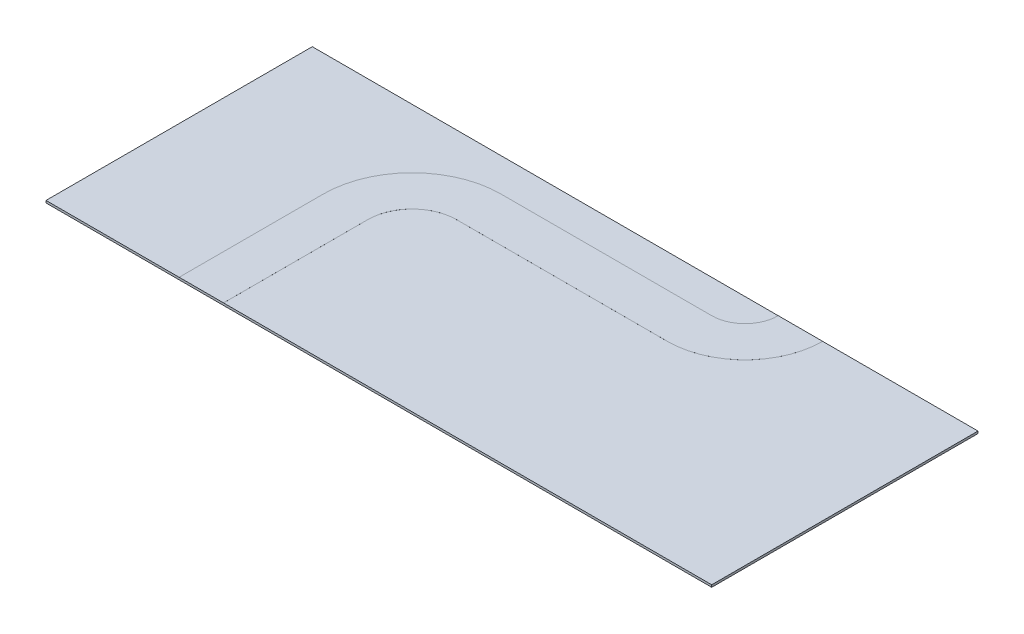
SolidWorks part; units mm, degrees
other "Kamera1"
ref_plane "Ebene vorne" through (0, 0, 0) normal (0, 0, 1) x (1, 0, 0)
ref_plane "Ebene oben" through (0, 0, 0) normal (0, 1, 0) x (1, 0, 0)
ref_plane "Ebene rechts" through (0, 0, 0) normal (1, 0, 0) x (0, 0, -1)
sketch "Skizze1" plane through (0, 0, 0) normal (0, 1, 0) x (1, 0, 0)
  line L1 (-1500, 600) -> (1500, 600)
  line L2 (-1500, 600) -> (-1500, -600)
  line L3 (-1500, -600) -> (1500, -600)
  line L4 (1500, 600) -> (1500, -600)
  line L5 (-1500, 600) -> (1500, -600) construction
  line L6 (-1500, -600) -> (1500, 600) construction
  point P0 (0, 0)
  dimension "D1" = 3000
  dimension "D2" = 1200
extrude "Boden" add sketch "Skizze1" along normal blind 10
sketch "Skizze2" plane through (0, 10, 0) normal (0, 1, 0) x (1, 0, 0)
  line L0 (-800, -600) -> (-800, 50) construction
  line L1 (-1500, -600) -> (1500, -600) construction
  line L2 (-500, 350) -> (450, 350) construction
  line L3 (1500, 600) -> (-1500, 600) construction
  line L6 (-700, -600) -> (-700, 50)
  line L7 (-500, 250) -> (450, 250)
  line L8 (-900, -600) -> (-900, 50)
  line L9 (-500, 450) -> (450, 450)
  line L10 (0, 0) -> (0, 756.6063) construction
  line L11 (800, 600) -> (600, 600)
  line L12 (-700, -600) -> (-900, -600)
  arc A0 (-800, 50) -> (-500, 350) centre (-500, 50) cw construction
  arc A1 (450, 350) -> (700, 600) centre (450, 600) ccw construction
  arc A2 (-700, 50) -> (-500, 250) centre (-500, 50) cw
  arc A3 (450, 250) -> (800, 600) centre (450, 600) ccw
  arc A4 (-900, 50) -> (-500, 450) centre (-500, 50) cw
  arc A5 (450, 450) -> (600, 600) centre (450, 600) ccw
  dimension "D2" = 300
  dimension "D4" = 800
  dimension "D1" = 700
  dimension "D3" = 950
  dimension "D5" = 100
  dimension "D6" = 100
extrude "Bahn" add sketch "Skizze2" along normal blind 0.1
